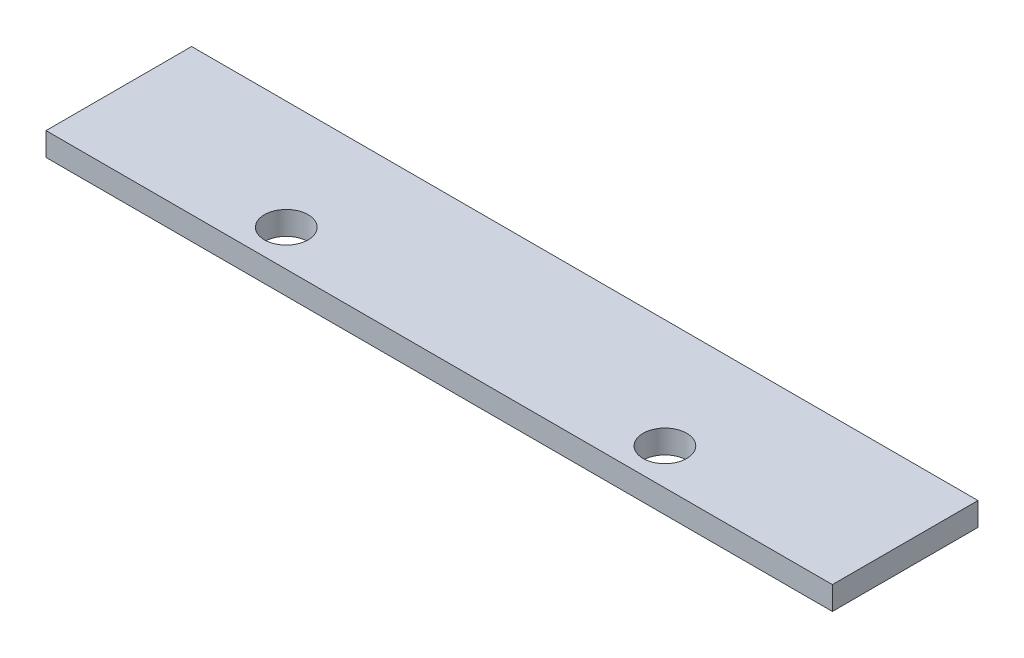
SolidWorks part; units mm, degrees
ref_plane "Front Plane" through (0, 0, 0) normal (0, 0, 1) x (1, 0, 0)
ref_plane "Top Plane" through (0, 0, 0) normal (0, 1, 0) x (1, 0, 0)
ref_plane "Right Plane" through (0, 0, 0) normal (1, 0, 0) x (0, 0, -1)
sketch "Sketch1" plane through (0, 0, 0) normal (0, 1, 0) x (1, 0, 0)
  line L0 (0, 0) -> (0, -5) construction
  line L1 (-27, 5) -> (27, 5)
  line L2 (-27, 5) -> (-27, -5)
  line L3 (-27, -5) -> (27, -5)
  line L4 (27, 5) -> (27, -5)
  line L5 (-27, 5) -> (27, -5) construction
  line L6 (-27, -5) -> (27, 5) construction
  line L7 (-13, -2.5) -> (13, -2.5) construction
  circle A0 centre (-13, -2.5) radius 1.5
  circle A1 centre (13, -2.5) radius 1.5
  point P0 (0, 0)
  point P11 (0, -2.5)
  dimension "D5" = 3
  dimension "D1" = 54
  dimension "D2" = 10
  dimension "D3" = 26
  dimension "D4" = 2.5
extrude "Boss-Extrude1" add sketch "Sketch1" along normal blind 1.6
